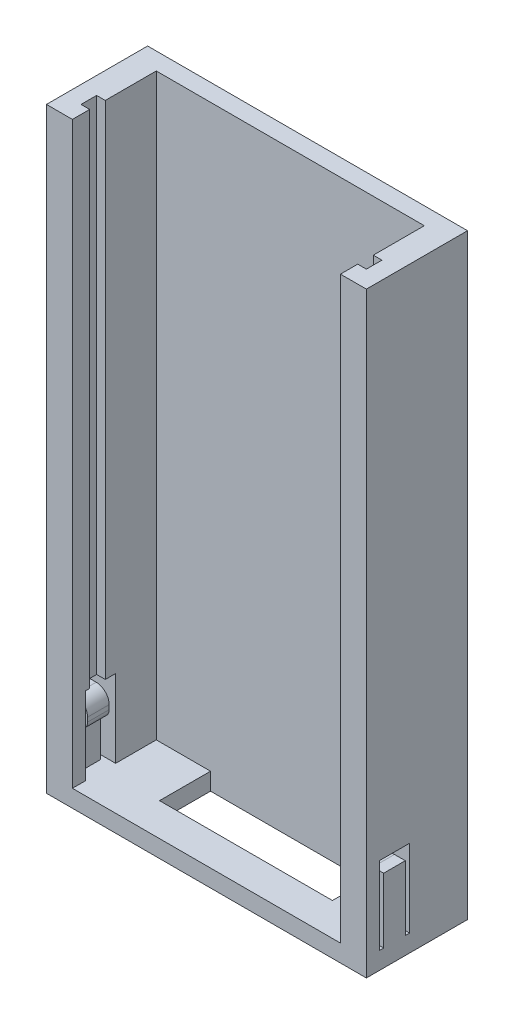
SolidWorks part; units mm, degrees
ref_plane "Front Plane" through (0, 0, 0) normal (0, 0, 1) x (1, 0, 0)
ref_plane "Top Plane" through (0, 0, 0) normal (0, 1, 0) x (1, 0, 0)
ref_plane "Right Plane" through (0, 0, 0) normal (1, 0, 0) x (0, 0, -1)
sketch "Sketch1" plane through (0, 0, 0) normal (0, 1, 0) x (1, 0, 0)
  line L1 (0, 0) -> (37, 0)
  line L2 (0, 0) -> (0, 11.7)
  line L3 (0, 11.7) -> (37, 11.7)
  line L4 (37, 0) -> (37, 11.7)
  dimension "D1" = 37
  dimension "D2" = 11.7
extrude "Boss-Extrude1" add sketch "Sketch1" along normal blind 69
sketch "Sketch2" plane through (0, 69, 0) normal (0, 1, 0) x (1, 0, 0)
  line L0 (3, 0) -> (3, 2)
  line L1 (0, 0) -> (37, 0) construction
  line L2 (3, 2) -> (2, 2)
  line L4 (3, 9.7) -> (34, 9.7)
  line L7 (35, 2) -> (34, 2)
  line L8 (34, 2) -> (34, 0)
  line L9 (3, 0) -> (34, 0)
  line L10 (37, 11.7) -> (0, 11.7) construction
  line L13 (3, 9.7) -> (3, 3.8)
  line L14 (3, 3.8) -> (2, 3.8)
  line L15 (2, 3.8) -> (2, 2)
  line L16 (35, 2) -> (35, 3.8)
  line L17 (35, 3.8) -> (34, 3.8)
  line L18 (34, 3.8) -> (34, 9.7)
  point P11 (18.5, 0)
  point P12 (18.5, 0)
  dimension "D1" = 2
  dimension "D2" = 1.8
  dimension "D3" = 2
  dimension "D4" = 33
  dimension "D5" = 1
extrude "Cut-Extrude1" cut sketch "Sketch2" against normal blind 67
sketch "Sketch3" plane through (0, 2, 0) normal (0, 1, 0) x (1, 0, 0)
  line L0 (34, 9.7) -> (3, 9.7) construction
  line L1 (9.275, 9.7) -> (29.275, 9.7)
  line L2 (9.275, 9.7) -> (9.275, 3.8)
  line L3 (9.275, 3.8) -> (29.275, 3.8)
  line L4 (29.275, 9.7) -> (29.275, 3.8)
  line L5 (35, 3.8) -> (34, 3.8) construction
  line L6 (3, 9.7) -> (3, 3.8) construction
  dimension "D1" = 20
  dimension "D2" = 6.275
extrude "Cut-Extrude2" cut sketch "Sketch3" against normal blind 67
sketch "Sketch4" plane through (48.7, 0, -11.7) normal (0, 0, -1) x (-1, 0, 0)
  line L2 (48.7, 55.9) -> (52.5, 55.9)
  line L3 (52.5, 48.1) -> (48.7, 48.1)
  line L4 (48.7, 19.9) -> (52.5, 19.9)
  line L5 (52.5, 12.1) -> (48.7, 12.1)
  line L6 (48.7, 55.9) -> (48.7, 48.1)
  line L7 (48.7, 19.9) -> (48.7, 12.1)
  line L8 (11.7, 69) -> (48.7, 69) construction
  line L9 (48.7, 69) -> (48.7, 0) construction
  circle A0 centre (52.5, 52) radius 1.9
  circle A1 centre (52.5, 16) radius 1.9
  arc A2 (52.5, 55.9) -> (52.5, 48.1) centre (52.5, 52) cw
  arc A3 (52.5, 19.9) -> (52.5, 12.1) centre (52.5, 16) cw
  dimension "D4" = 3.8
  dimension "D5" = 2
  dimension "D6" = 2
  dimension "D1" = 3.8
  dimension "D2" = 36
  dimension "D3" = 17
extrude "Boss-Extrude2" add sketch "Sketch4" against normal blind 3
fillet "Fillet1" radius 2 4 edges at (0, 12.1, -10.2) (0, 48.1, -10.2) (0, 19.9, -10.2) (0, 55.9, -10.2)
sketch "Sketch5" plane through (37, 0, 0) normal (1, 0, 0) x (0, 0, -1)
  line L0 (0, 69) -> (0, 0) construction
  line L1 (1.5, 2) -> (5, 2)
  line L2 (1.5, 2) -> (1.5, 11)
  line L3 (1.5, 11) -> (5, 11)
  line L4 (5, 2) -> (5, 11)
  line L6 (0, 0) -> (11.7, 0) construction
  dimension "D1" = 1.5
  dimension "D2" = 2
  dimension "D3" = 3.5
  dimension "D4" = 9
extrude "Cut-Extrude3" cut sketch "Sketch5" against normal blind 40
sketch "Sketch6" plane through (0, 0, -1.5) normal (0, 0, -1) x (-1, 0, 0)
  line L0 (0, 2) -> (0, 9.5)
  line L1 (0, 2) -> (0, 11) construction
  line L2 (0, 9.5) -> (-1.25, 9.5)
  line L3 (-2.75, 8) -> (-2.75, 7.5)
  line L4 (-1.75, 6.5) -> (-1.75, 2)
  line L5 (0, 2) -> (-3, 2) construction
  line L6 (0, 2) -> (-1.75, 2)
  arc A0 (-1.25, 9.5) -> (-2.75, 8) centre (-1.25, 8) ccw
  arc A1 (-2.75, 7.5) -> (-1.75, 6.5) centre (-1.75, 7.5) ccw
  dimension "D3" = 1
  dimension "D1" = 1.75
  dimension "D2" = 1.25
  dimension "D4" = 7.5
  dimension "D5" = 4.5
extrude "Boss-Extrude3" add sketch "Sketch6" along normal blind 2.5 from offset 0.5
ref_plane "Plane1" through (18.5, 0, 0) normal (-1, 0, 0) x (0, 0, 1)
mirror "Mirror1" about plane through (18.5, 0, 0) normal (-1, 0, 0) of "Boss-Extrude3"
